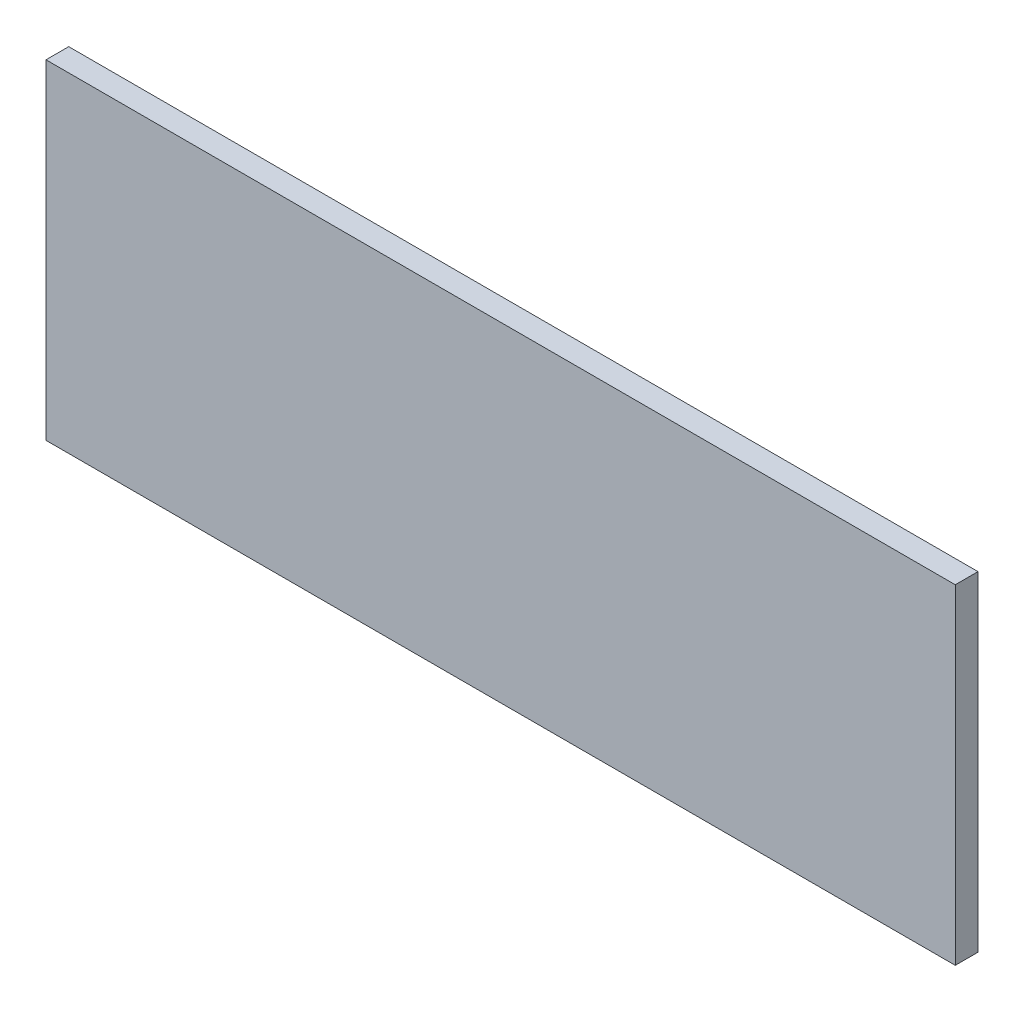
SolidWorks part; units mm, degrees
ref_plane "前视基准面" through (0, 0, 0) normal (0, 0, 1) x (1, 0, 0)
ref_plane "上视基准面" through (0, 0, 0) normal (0, 1, 0) x (1, 0, 0)
ref_plane "右视基准面" through (0, 0, 0) normal (1, 0, 0) x (0, 0, -1)
sketch "草图1" plane through (0, 0, 0) normal (0, 0, 1) x (1, 0, 0)
  line L1 (0, 0) -> (80, 0)
  line L2 (0, 0) -> (0, 29)
  line L3 (0, 29) -> (80, 29)
  line L4 (80, 0) -> (80, 29)
  dimension "D1" = 80
  dimension "D2" = 29
extrude "凸台-拉伸1" add sketch "草图1" along normal blind 2
